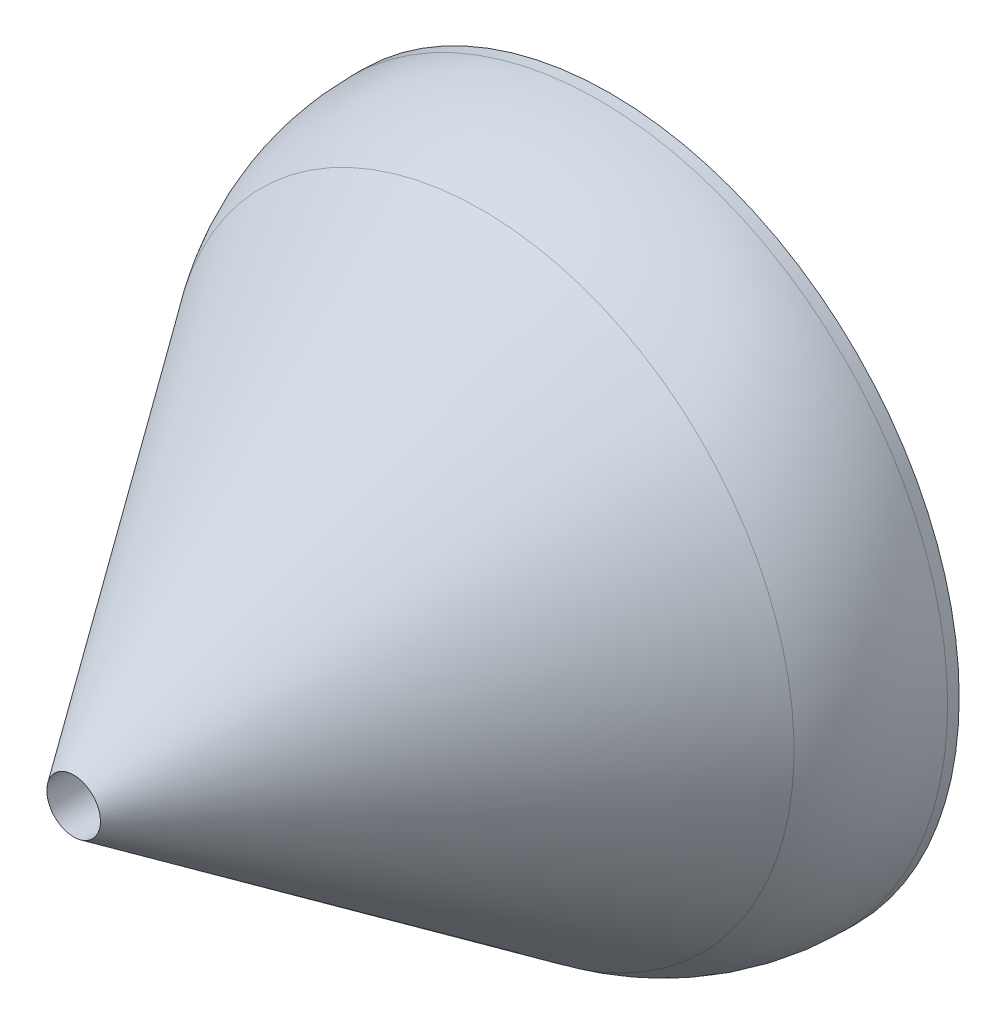
SolidWorks part; units mm, degrees
ref_plane "Front Plane" through (0, 0, 0) normal (1, 0, 0) x (0, 1, 0)
ref_plane "Top Plane" through (0, 0, 0) normal (0, 0, 1) x (0, 1, 0)
ref_plane "Right Plane" through (0, 0, 0) normal (0, 1, 0) x (-1, 0, 0)
sketch "Sketch2" plane through (0, 0, 0) normal (1, 0, 0) x (0, 1, 0)
  line L19 (0, 0) -> (0, 338.517) construction
  line L22 (-63.5, 0) -> (-63.5, 17.928)
  line L23 (-63.5, 17.928) -> (-36.3371, 56.8087)
  line L24 (-36.3371, 56.8087) -> (-6.35, 56.8087)
  line L25 (-6.35, 56.8087) -> (-6.35, 69.5087)
  line L26 (-6.35, 69.5087) -> (-27.4646, 69.5087)
  line L27 (-27.4646, 69.5087) -> (-6.35, 99.732)
  line L29 (-82.55, 17.928) -> (-6.35, 127)
  line L34 (-82.55, 17.928) -> (-82.55, 0)
  line L36 (-82.55, 0) -> (-63.5, 0)
  line L37 (-6.35, 127) -> (-6.35, 99.732)
  point P1 (-88.8993, 0.345)
  point P11 (-76.2, 1.3075)
  point P13 (-76.2, 3.8679)
  point P15 (-63.0342, 24.709)
  dimension "D1" = 82.55
  dimension "D2" = 63.5
  dimension "D3" = 12.7
  dimension "D4" = 12.7
  dimension "D5" = 12.7
  dimension "D6" = 127
revolve "Revolve1" add sketch "Sketch2" angle 360 about L19
fillet "Fillet1" radius 48.26 1 edges at (-82.55, 0, 17.928)
